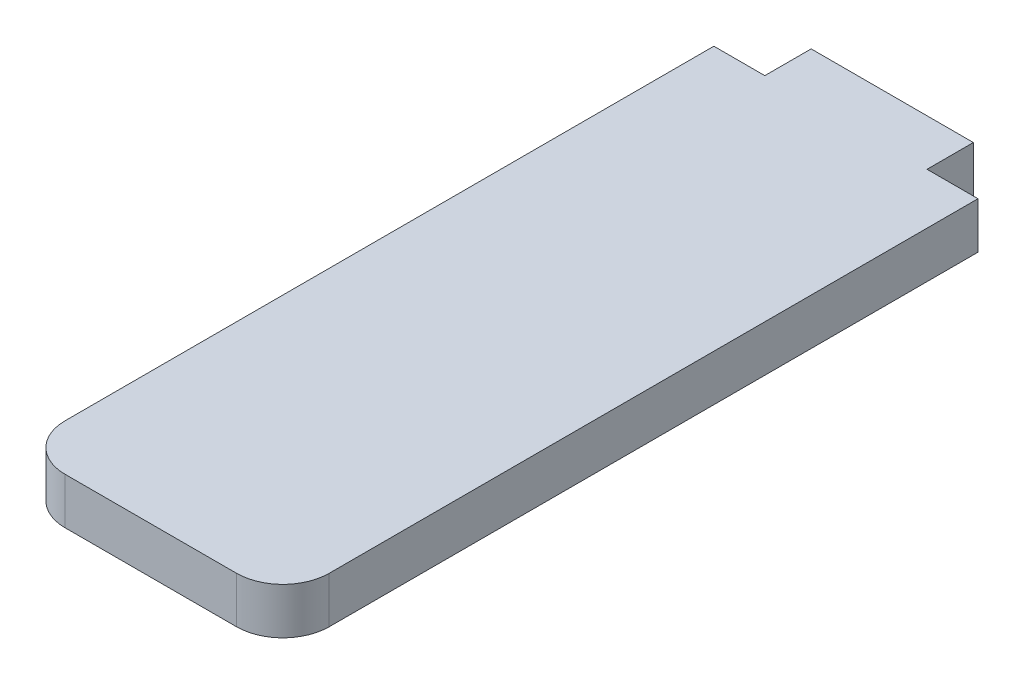
SolidWorks part; units mm, degrees
ref_plane "Front Plane" through (0, 0, 0) normal (0, 0, 1) x (1, 0, 0)
ref_plane "Top Plane" through (0, 0, 0) normal (0, 1, 0) x (1, 0, 0)
ref_plane "Right Plane" through (0, 0, 0) normal (1, 0, 0) x (0, 0, -1)
sketch "Sketch1" plane through (0, 0, 0) normal (0, 1, 0) x (1, 0, 0)
  line L0 (8.75, -2.5) -> (14.25, -2.5)
  line L2 (-8.75, -2.5) -> (-8.75, 2.5)
  line L3 (-8.75, 2.5) -> (8.75, 2.5)
  line L4 (8.75, -2.5) -> (8.75, 2.5)
  line L5 (-8.75, -2.5) -> (8.75, 2.5) construction
  line L6 (-8.75, 2.5) -> (8.75, -2.5) construction
  line L7 (-9.25, -77.5) -> (9.25, -77.5)
  line L8 (-14.25, -72.5) -> (-14.25, -2.5)
  line L9 (-14.25, -2.5) -> (-8.75, -2.5)
  line L10 (14.25, -72.5) -> (14.25, -2.5)
  line L11 (-14.25, -77.5) -> (14.25, -2.5) construction
  line L12 (-14.25, -2.5) -> (14.25, -77.5) construction
  arc A0 (9.25, -77.5) -> (14.25, -72.5) centre (9.25, -72.5) ccw
  arc A1 (-9.25, -77.5) -> (-14.25, -72.5) centre (-9.25, -72.5) cw
  point P0 (0, 0)
  point P5 (0, -40)
  dimension "D5" = 5
  dimension "D1" = 5
  dimension "D2" = 17.5
  dimension "D3" = 28.5
  dimension "D4" = 75
extrude "Boss-Extrude1" add sketch "Sketch1" along normal blind 5
